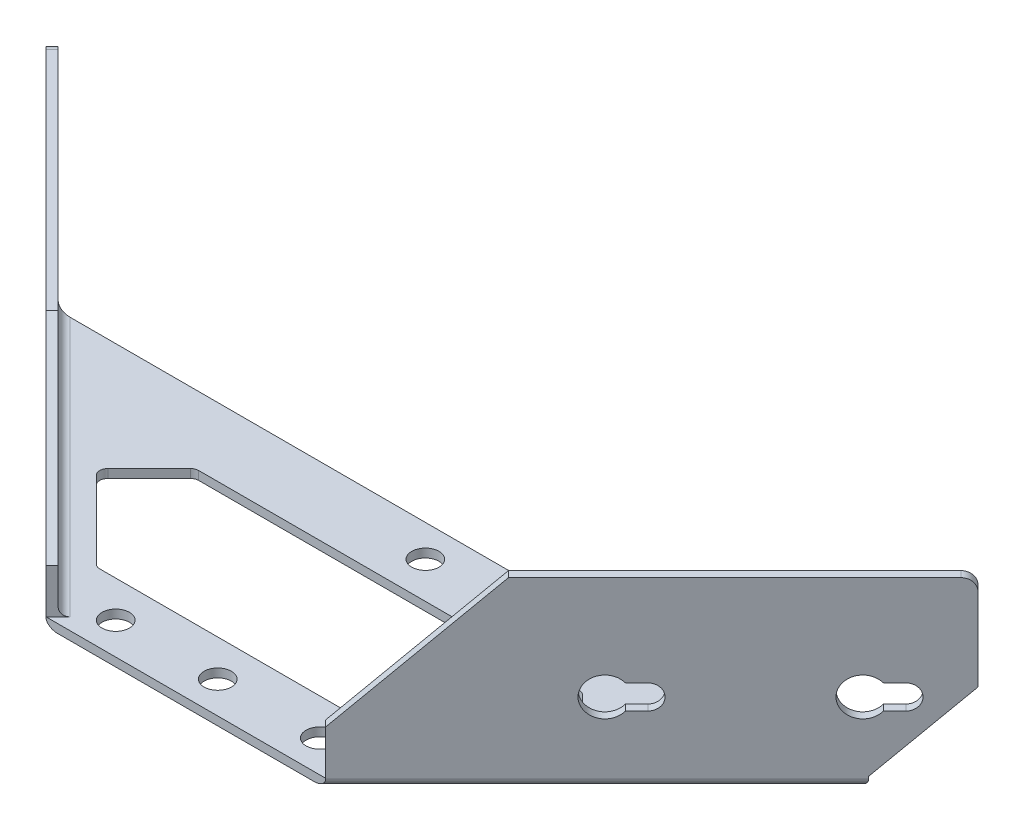
SolidWorks part; units mm, degrees
ref_plane "Front Plane" through (0, 0, 0) normal (0, 0, 1) x (1, 0, 0)
ref_plane "Top Plane" through (0, 0, 0) normal (0, 1, 0) x (1, 0, 0)
ref_plane "Right Plane" through (0, 0, 0) normal (1, 0, 0) x (0, 0, -1)
sketch "Sketch1" plane through (0, 0, 0) normal (0, 1, 0) x (1, 0, 0)
  line L0 (0, 0) -> (46, 0)
  line L1 (46, 0) -> (90.65, 44.65)
  line L2 (90.65, 44.65) -> (-44.65, 44.65)
  line L3 (-44.65, 44.65) -> (0, 0)
  line L4 (-16.981, 25.2683) -> (-2.9627, 11.25)
  line L5 (-2.9627, 11.25) -> (48.9627, 11.25)
  line L6 (48.9627, 11.25) -> (62.981, 25.2683)
  line L7 (62.981, 25.2683) -> (54.8493, 33.4)
  line L8 (54.8493, 33.4) -> (-8.8493, 33.4)
  line L9 (-8.8493, 33.4) -> (-16.981, 25.2683)
  circle A0 centre (23, 39.4) radius 2.25
  circle A1 centre (23, 5.25) radius 2.25
  circle A2 centre (39.7807, 5.25) radius 2.25
  circle A3 centre (6.2193, 5.25) radius 2.25
  dimension "D10" = 4.5
  dimension "D1" = 46
  dimension "D2" = 135
  dimension "D3" = 135
  dimension "D4" = 44.65
  dimension "D5" = 11.25
  dimension "D6" = 11.25
  dimension "D7" = 5.86
  dimension "D8" = 5.86
  dimension "D9" = 11.5
  dimension "D11" = 5.25
  dimension "D12" = 5.25
  dimension "D13" = 23
extrude "BaseBoss-Extrude1" add sketch "Sketch1" along normal blind 1.42
sketch "Sketch2" plane through (0, 1.42, 0) normal (0, 1, 0) x (1, 0, 0)
  line L0 (-52.6418, 54.65) -> (1.0041, 1.0041)
  line L1 (1.0041, 1.0041) -> (0, 0)
  line L2 (-44.65, 44.65) -> (0, 0) construction
  line L3 (0, 0) -> (-53.6459, 53.6459)
  line L4 (-53.6459, 53.6459) -> (-52.6418, 54.65)
  line L5 (90.65, 44.65) -> (-44.65, 44.65) construction
  line L6 (44.9959, 1.0041) -> (46, 0)
  line L7 (46, 0) -> (90.65, 44.65) construction
  line L8 (46, 0) -> (99.6459, 53.6459)
  line L9 (99.6459, 53.6459) -> (98.6418, 54.65)
  line L10 (98.6418, 54.65) -> (44.9959, 1.0041)
  dimension "D1" = 10
  dimension "D2" = 1.42
extrude "WingBoss-Extrude2" add sketch "Sketch2" along normal blind 28.58
chamfer "FrontChamfer1" distance 21.26 angle 45 2 edges at (45.498, 30, -0.502) (0.502, 30, -0.502)
chamfer "BackChamfer3" distance 13 angle 45 2 edges at (-53.1439, 1.42, -54.148) (99.1439, 1.42, -54.148)
fillet "BackCornerFillet1" radius 2 2 edges at (99.1439, 30, -54.148) (-53.1439, 30, -54.148)
sketch "Sketch3" plane through (1.0041, 0, -1.0041) normal (0.7071, 0, -0.7071) x (-0.7071, 0, -0.7071)
  line L0 (62.4731, 13) -> (67.4731, 13) construction
  line L1 (64.8706, 15.0043) -> (67.4731, 15.0044)
  line L2 (64.8706, 10.9957) -> (67.4783, 10.9957)
  line L3 (32.4731, 13) -> (37.4731, 13) construction
  line L4 (34.8706, 15.0043) -> (37.4731, 15)
  line L5 (34.8706, 10.9957) -> (37.4731, 11)
  line L6 (-32.5269, 0) -> (63.1446, 0) construction
  line L9 (-32.5269, 1.6979) -> (-32.5269, 14.42) construction
  arc A0 (34.8706, 15.0043) -> (34.8706, 10.9957) centre (32.4731, 13) ccw
  arc A1 (64.8706, 15.0043) -> (64.8706, 10.9957) centre (62.4731, 13) ccw
  arc A3 (67.4783, 10.9957) -> (67.4731, 15.0044) centre (67.4731, 13) ccw
  arc A5 (37.4731, 11) -> (37.4731, 15) centre (37.4731, 13) ccw
  point P5 (64.3668, 15.68)
  point P10 (34.3668, 15.68)
  dimension "D1" = 6.25
  dimension "D4" = 4
  dimension "D2" = 5
  dimension "D3" = 30
  dimension "D6" = 65
  dimension "D5" = 13
extrude "RightWingCut-Extrude1" cut sketch "Sketch3" against normal through all
sketch "Sketch4" plane through (21.9959, 0, 21.9959) normal (-0.7071, 0, -0.7071) x (-0.7071, 0, 0.7071)
  line L0 (-95.6715, 0) -> (0, 0) construction
  line L1 (0, 14.42) -> (0, 1.6979) construction
  line L2 (-95, 13) -> (-100, 13) construction
  line L3 (-97.3975, 10.9957) -> (-100.0052, 10.9957)
  line L4 (-97.3975, 15.0043) -> (-100, 15.0044)
  line L5 (-65, 13) -> (-70, 13) construction
  line L6 (-67.3975, 10.9957) -> (-70, 11)
  line L7 (-67.3975, 15.0043) -> (-70, 15)
  arc A0 (-97.3975, 10.9957) -> (-97.3975, 15.0043) centre (-95, 13) ccw
  arc A1 (-67.3975, 10.9957) -> (-67.3975, 15.0043) centre (-65, 13) ccw
  arc A3 (-100, 15.0044) -> (-100.0052, 10.9957) centre (-100, 13) ccw
  arc A5 (-70, 15) -> (-70, 11) centre (-70, 13) ccw
  point P8 (-96.8937, 15.68)
  point P14 (-66.8937, 15.68)
  dimension "D1" = 6.25
  dimension "D5" = 4
  dimension "D2" = 30
  dimension "D6" = 5
  dimension "D3" = 65
  dimension "D4" = 13
extrude "LeftWingCut-Extrude2" cut sketch "Sketch4" against normal through all
fillet "outsideWingFillet2" radius 1.35 2 edges at (68.325, 0, -22.325) (-22.325, 0, -22.325)
fillet "InsideWingFillet3" radius 1.35 2 edges at (-20.8189, 1.42, -22.827) (66.8189, 1.42, -22.827)
fillet "InsideCutoutFillet4" radius 1.35 6 edges at (-16.981, 0.71, -25.2683) (62.981, 0.71, -25.2683) (-2.9627, 0.71, -11.25) (48.9627, 0.71, -11.25) (54.8493, 0.71, -33.4) (-8.8493, 0.71, -33.4)
equation "\"AngleBracketThickness\"= 1.42mm"
equation "\"D1@BaseBoss-Extrude1\" = \"AngleBracketThickness\""
equation "\"D2@Sketch2\"=\"AngleBracketThickness\""
equation "\"D1@WingBoss-Extrude2\" = \"AngleBracketWingHeight\" - \"AngleBracketThickness\""
equation "\"AngleBracketWingHeight\"= 30mm"
equation "\"AngleBracketSlotDistanceBetweenHoles\"= 30mm"
equation "\"D3@Sketch3\"=\"AngleBracketSlotDistanceBetweenHoles\""
equation "\"AngleBracketLargeHoleDiameter\"= 6.25mm"
equation "\"D1@Sketch3\"=\"AngleBracketLargeHoleDiameter\""
equation "\"AngleBracketSmallHoleDiameter\"= 4mm"
equation "\"D4@Sketch3\"=\"AngleBracketSmallHoleDiameter\""
equation "\"AngleBracketSlotLength\"= 5mm"
equation "\"D2@Sketch3\"=\"AngleBracketSlotLength\""
equation "\"AngleBracketSlotDistanceFromBack\"= 65mm"
equation "\"AngleBracketSlotDistanceFromTop\"= 13mm"
equation "\"D2@Sketch4\"=\"AngleBracketSlotDistanceBetweenHoles\""
equation "\"D1@Sketch4\"=\"AngleBracketLargeHoleDiameter\""
equation "\"D5@Sketch4\"=\"AngleBracketSmallHoleDiameter\""
equation "\"D6@Sketch4\"=\"AngleBracketSlotLength\""
equation "\"D6@Sketch3\"=\"AngleBracketSlotDistanceFromBack\""
equation "\"D3@Sketch4\"=\"AngleBracketSlotDistanceFromBack\""
equation "\"D5@Sketch3\"=\"AngleBracketSlotDistanceFromTop\""
equation "\"D4@Sketch4\"=\"AngleBracketSlotDistanceFromTop\""
